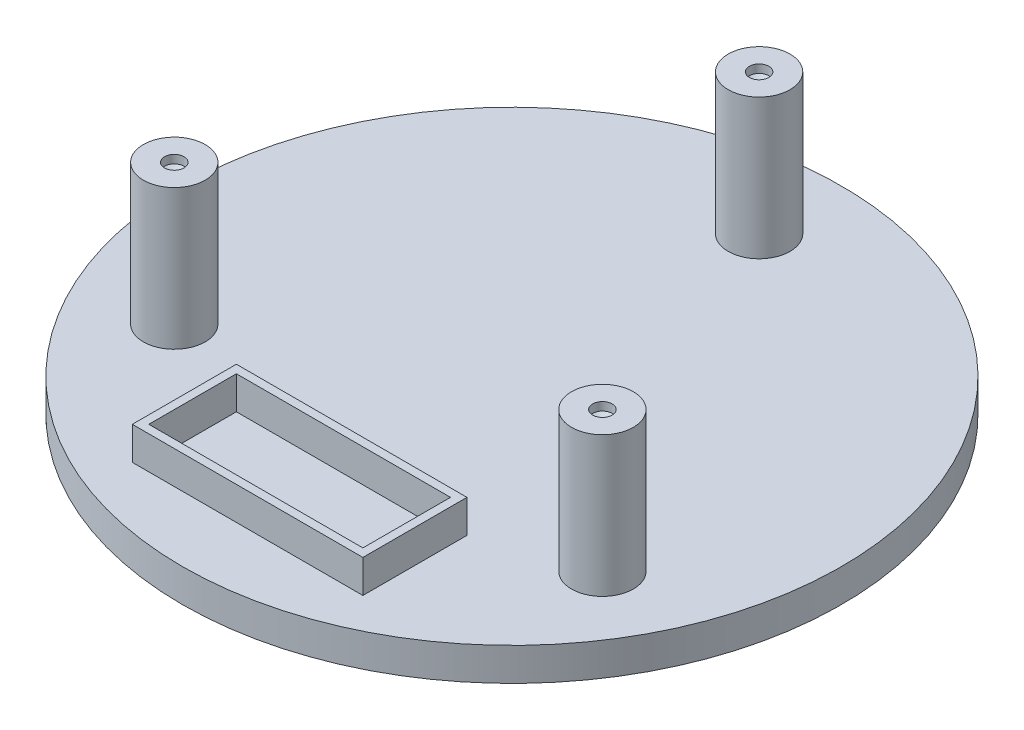
SolidWorks part; units mm, degrees
ref_plane "Front Plane" through (0, 0, 0) normal (0, 0, 1) x (1, 0, 0)
ref_plane "Top Plane" through (0, 0, 0) normal (0, 1, 0) x (1, 0, 0)
ref_plane "Right Plane" through (0, 0, 0) normal (1, 0, 0) x (0, 0, -1)
sketch "Sketch1" plane through (0, 0, 0) normal (0, 0, 1) x (1, 0, 0)
  line L0 (0, 0) -> (-50.8, 0)
  line L1 (-50.8, 0) -> (-50.8, -5.08)
  line L2 (-50.8, -5.08) -> (-38.1, -5.08)
  line L3 (-38.1, -5.08) -> (-38.1, -2.54)
  line L4 (-38.1, -2.54) -> (0, -2.54)
  line L5 (0, -2.54) -> (0, 0)
  dimension "D1" = 50.8
  dimension "D2" = 12.7
  dimension "D3" = 5.08
  dimension "D4" = 2.54
sketch "Sketch2" plane through (0, 0, 0) normal (0, 0, 1) x (1, 0, 0)
  line L0 (0, 4.5677) -> (0, -8.0056) construction
revolve "Revolve1" add sketch "Sketch1" angle 360 about L0
sketch "Sketch3" plane through (0, 0, 0) normal (0, 1, 0) x (1, 0, 0)
  line L0 (0, 0) -> (0, 38.1) construction
  line L1 (0, 0) -> (-32.9956, -19.05) construction
  line L2 (0, 0) -> (32.9956, -19.05) construction
  circle A0 centre (0, 38.1) radius 4.7625
  circle A1 centre (-32.9956, -19.05) radius 4.7625
  circle A3 centre (32.9956, -19.05) radius 4.7625
  dimension "D2" = 38.1
  dimension "D3" = 120
  dimension "D1" = 9.525
  dimension "D4" = 120
extrude "Boss-Extrude1" add sketch "Sketch3" along normal blind 21.59
hole_wizard "M4x0.7 Tapped Hole1" positions "Sketch11" profile "Sketch10" tap size "M4x0.7" standard "ANSI Metric"
sketch "Sketch11" plane through (0, 21.59, 0) normal (0, 1, 0) x (1, 0, 0)
  point P0 (-32.9956, -19.05)
  point P3 (0, 38.1)
  point P6 (32.9956, -19.05)
sketch "Sketch10" plane through (-32.9956, 21.59, 19.05) normal (1, 0, 0) x (0, 0, 1)
  line L0 (0, 0) -> (0, 2.1713)
  line L1 (0, 2.1713) -> (1.5, 1.27)
  line L2 (1.5, 1.27) -> (1.5, 0)
  line L5 (1.5, 0) -> (0, 0)
  line L10 (0, 2.1713) -> (-1.5, 1.27) construction
  line L11 (0, -6.35) -> (0, 107.95) construction
  dimension "Tap Drill Dia." = 3
  dimension "Tap Drill Depth" = 1.27
  dimension "Drill Angle" = 118
sketch "Sketch12" plane through (0, 0, 0) normal (0, 1, 0) x (1, 0, 0)
  line L0 (0, 0) -> (0, -50.8) construction
  line L1 (-16.5, -39.4735) -> (16.5, -25.9735) construction
  line L2 (-16.5, -25.9735) -> (16.5, -25.9735)
  line L3 (-16.5, -25.9735) -> (-16.5, -39.4735)
  line L4 (-16.5, -39.4735) -> (16.5, -39.4735)
  line L5 (16.5, -25.9735) -> (16.5, -39.4735)
  line L6 (-17.77, -24.7035) -> (17.77, -24.7035)
  line L7 (17.77, -24.7035) -> (17.77, -40.7435)
  line L8 (-17.77, -40.7435) -> (17.77, -40.7435)
  line L9 (-17.77, -24.7035) -> (-17.77, -40.7435)
  line L10 (-17.77, -40.7435) -> (-20.3086, -46.564) construction
  line L11 (-20.3086, -46.564) -> (-15.8315, -48.5166) construction
  circle A0 centre (0, 0) radius 50.8 construction
  point P9 (0, -32.7235)
  dimension "D1" = 33
  dimension "D2" = 13.5
  dimension "D4" = 6.35
  dimension "D3" = 1.27
extrude "Boss-Extrude2" add sketch "Sketch12" along normal blind 5.08
